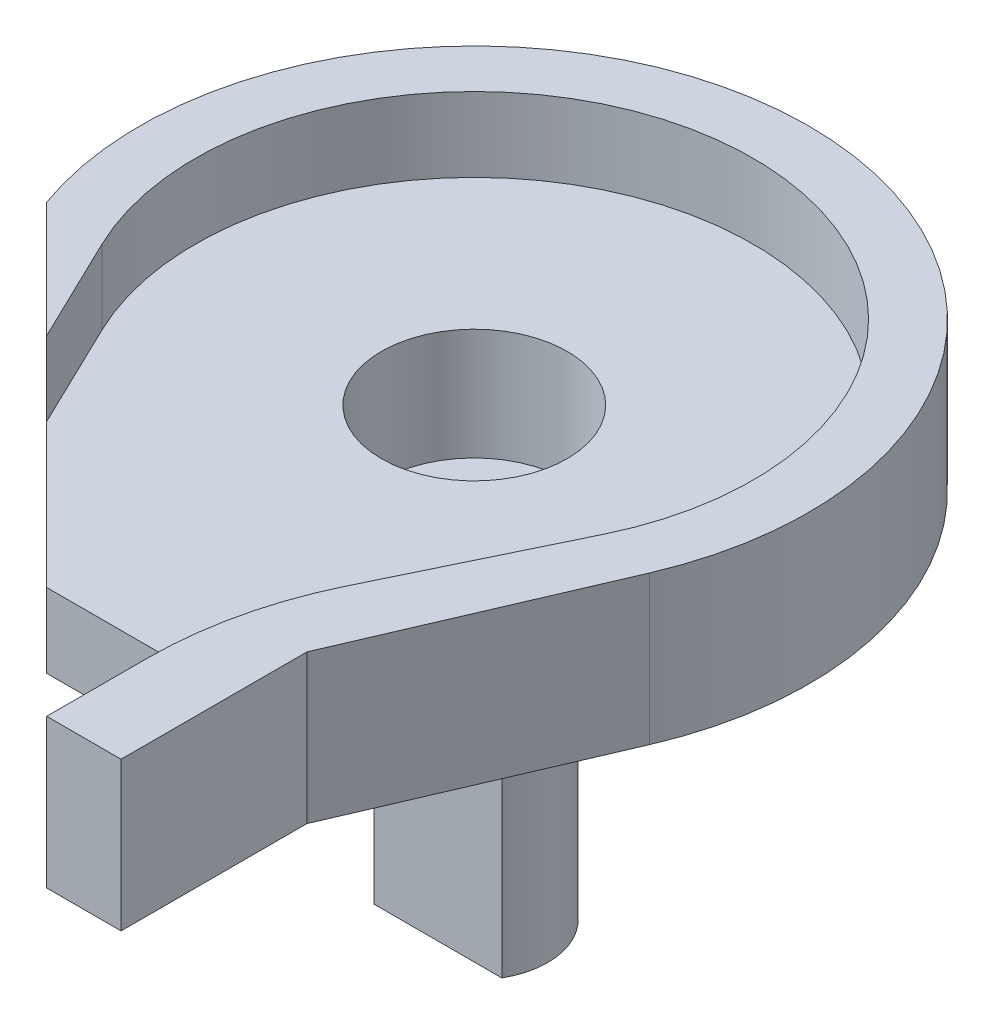
SolidWorks part; units mm, degrees
ref_plane "Front Plane" through (0, 0, 0) normal (0, 0, 1) x (1, 0, 0)
ref_plane "Top Plane" through (0, 0, 0) normal (0, 1, 0) x (1, 0, 0)
ref_plane "Right Plane" through (0, 0, 0) normal (1, 0, 0) x (0, 0, -1)
sketch "Sketch1" plane through (0, 0, 0) normal (0, 1, 0) x (1, 0, 0)
  line L1 (-8.2695, -3.5518) -> (-5.5, -10)
  line L2 (-5.5, -10) -> (5.5, -10)
  line L3 (5.5, -10) -> (8.2695, -3.5518)
  arc A0 (8.2695, -3.5518) -> (-8.2695, -3.5518) centre (0, 0) ccw
  point P12 (0, -10)
  dimension "D1" = 18
  dimension "D2" = 11
  dimension "D3" = 10
extrude "Boss-Extrude1" add sketch "Sketch1" along normal blind 4
sketch "Sketch2" plane through (0, 4, 0) normal (0, 1, 0) x (1, 0, 0)
  line L0 (-6.7539, -3.2611) -> (-3.5, -10)
  line L1 (-5.5, -10) -> (5.5, -10) construction
  line L2 (3.5, -10) -> (6.7539, -3.2611)
  line L3 (-3.5, -10) -> (3.5, -10)
  arc A0 (6.7539, -3.2611) -> (-6.7539, -3.2611) centre (0, 0) ccw
  point P9 (0, -10)
  dimension "D1" = 15
  dimension "D2" = 7
extrude "Cut-Extrude1" cut sketch "Sketch2" against normal blind 2
sketch "Sketch3" plane through (0, 0, 0) normal (0, -1, 0) x (1, 0, 0)
  line L0 (-1.7176, 0.975) -> (1.7176, 0.975)
  line L1 (-5.5, 10) -> (5.5, 10) construction
  line L2 (-2.9588, -1.975) -> (3.9837, -1.975) construction
  arc A0 (-1.7176, 0.975) -> (1.7176, 0.975) centre (0, 0) ccw
  dimension "D1" = 3.95
  dimension "D2" = 2.95
extrude "Boss-Extrude2" add sketch "Sketch3" along normal blind 10
sketch "Sketch4" plane through (0, 0, 0) normal (0, -1, 0) x (1, 0, 0)
  circle A0 centre (0, 0) radius 3
  dimension "D1" = 6
extrude "Boss-Extrude3" add sketch "Sketch4" along normal blind 4
sketch "Sketch5" plane through (0, 2, 0) normal (0, 1, 0) x (1, 0, 0)
  circle A0 centre (0, 0) radius 2.5
  dimension "D1" = 5
extrude "Cut-Extrude2" cut sketch "Sketch5" against normal blind 3
chamfer "Chamfer1" distance 1 angle 45 2 edges at (0, -4, -3) (0, 0, 3)
sketch "Sketch6" plane through (0, 0, 10) normal (0, 0, 1) x (1, 0, 0)
  line L1 (3.5, 4) -> (5.5, 4)
  line L2 (3.5, 4) -> (3.5, 0)
  line L3 (3.5, 0) -> (5.5, 0)
  line L4 (5.5, 4) -> (5.5, 0)
extrude "Boss-Extrude4" add sketch "Sketch6" along normal blind 5
fillet "Fillet1" radius 10 1 edges at (3.5, 3, 10)
sketch "Sketch8" plane through (0, 0, 0) normal (0, -1, 0) x (1, 0, 0)
  line L0 (-5.5, 10) -> (-1.5, 10)
  line L1 (-5.5, 10) -> (3.5, 10) construction
  line L2 (-1.5, 10) -> (-8.5114, 2.9886)
  line L3 (-8.2695, 3.5518) -> (-5.5, 10) construction
  line L4 (-8.5114, 2.9886) -> (-5.5, 10)
  dimension "D1" = 45
  dimension "D2" = 4
extrude "Cut-Extrude3" cut sketch "Sketch8" against normal blind 10
